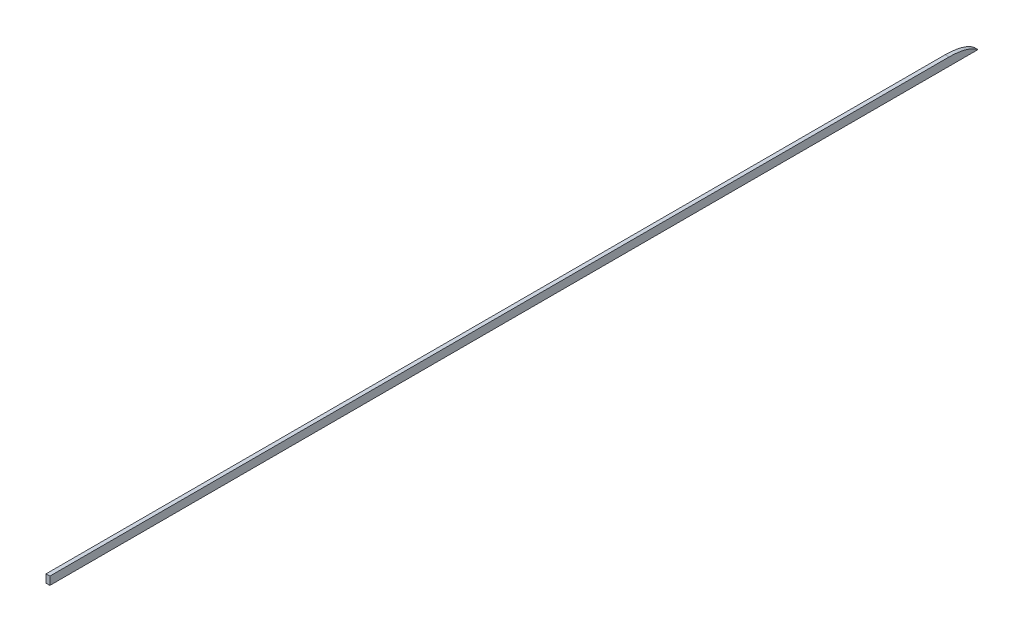
SolidWorks part; units mm, degrees
material "Free-Cutting Brass, UNS C36000"
ref_plane "Front Plane" through (0, 0, 0) normal (0, 0, 1) x (1, 0, 0)
ref_plane "Top Plane" through (0, 0, 0) normal (0, 1, 0) x (1, 0, 0)
ref_plane "Right Plane" through (0, 0, 0) normal (1, 0, 0) x (0, 0, -1)
sketch "Sketch1" plane through (0, 0, 0) normal (1, 0, 0) x (0, 0, -1)
  line L1 (0, 0) -> (304.8, 0)
  line L2 (0, 0) -> (0, 2.667)
  line L3 (0, 2.667) -> (295.275, 2.667)
  spline S0 degree 2 poles (304.8, 0) (301.6047, 2.5668) (295.275, 2.667) knots 0 0 0 1 1 1
  dimension "D1" = 2.667
  dimension "D2" = 304.8
  dimension "D3" = 9.525
extrude "Boss-Extrude1" add sketch "Sketch1" along normal blind 1.27
